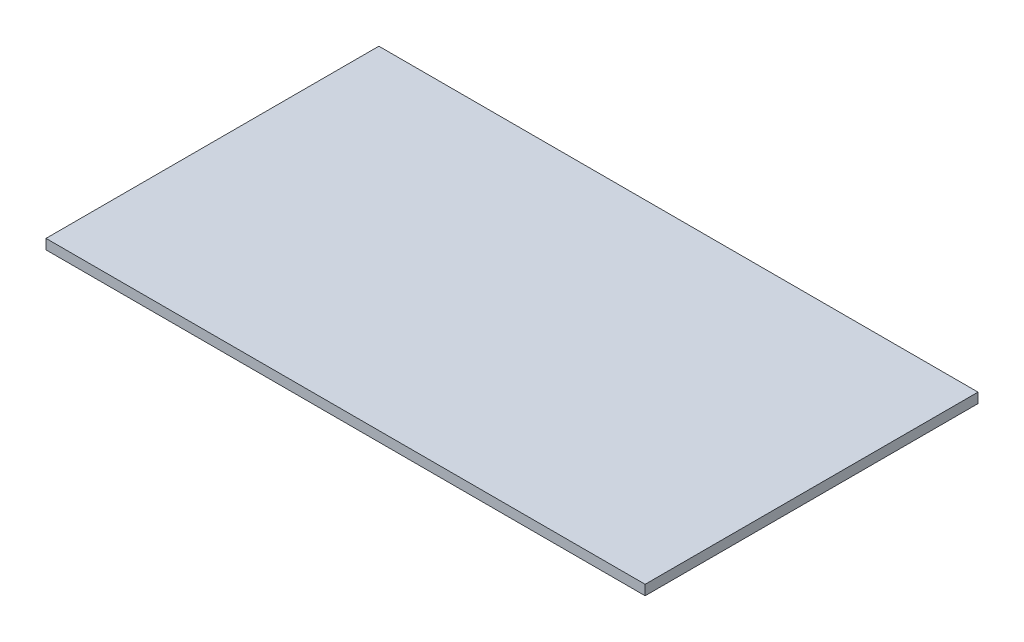
SolidWorks part; units mm, degrees
ref_plane "Front Plane" through (0, 0, 0) normal (0, 0, 1) x (1, 0, 0)
ref_plane "Top Plane" through (0, 0, 0) normal (0, 1, 0) x (1, 0, 0)
ref_plane "Right Plane" through (0, 0, 0) normal (1, 0, 0) x (0, 0, -1)
sketch "Sketch1" plane through (0, 0, 0) normal (0, 1, 0) x (1, 0, 0)
  line L1 (-540, -300) -> (540, -300)
  line L2 (-540, -300) -> (-540, 300)
  line L3 (-540, 300) -> (540, 300)
  line L4 (540, -300) -> (540, 300)
  line L5 (-540, -300) -> (540, 300) construction
  line L6 (-540, 300) -> (540, -300) construction
  point P0 (0, 0)
  dimension "D1" = 1080
  dimension "D2" = 600
extrude "Boss-Extrude1" add sketch "Sketch1" along normal blind 18
